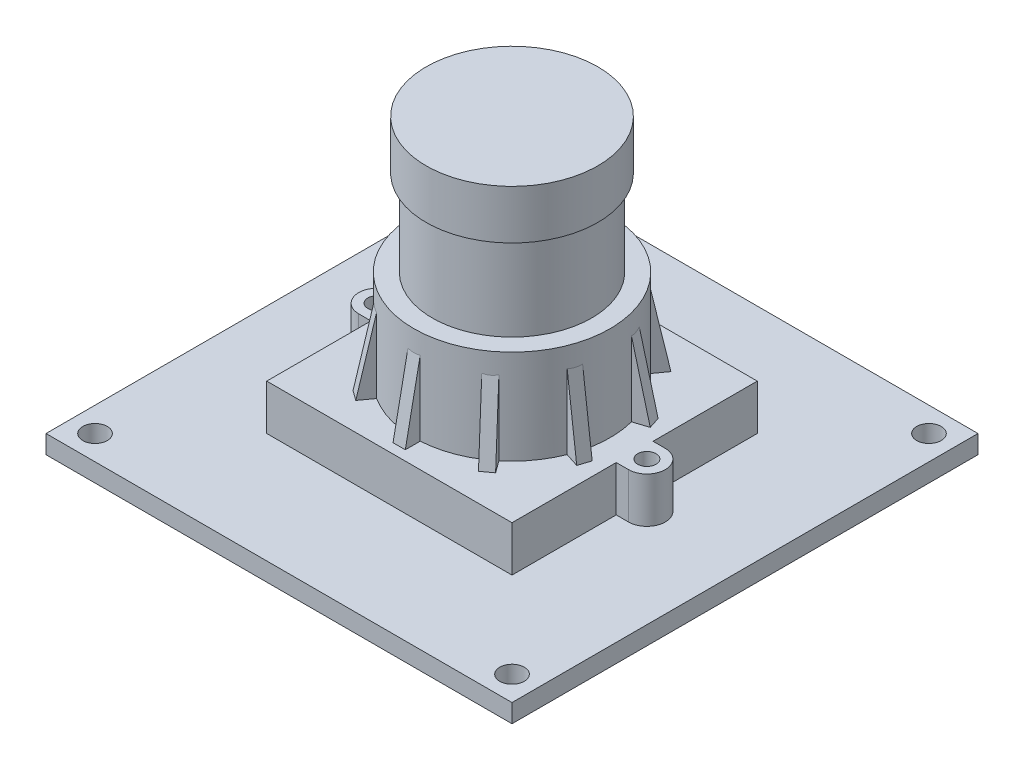
SolidWorks part; units mm, degrees
material "ABS"
ref_plane "前视基准面" through (0, 0, 0) normal (0, 0, 1) x (1, 0, 0)
ref_plane "上视基准面" through (0, 0, 0) normal (0, 1, 0) x (1, 0, 0)
ref_plane "右视基准面" through (0, 0, 0) normal (1, 0, 0) x (0, 0, -1)
sketch "草图1" plane through (0, 0, 0) normal (0, 1, 0) x (1, 0, 0)
  line L0 (0, 19) -> (0, -19) construction
  line L1 (-19, -19) -> (19, -19)
  line L2 (-19, -19) -> (-19, 19)
  line L3 (-19, 19) -> (19, 19)
  line L4 (19, -19) -> (19, 19)
  line L5 (-19, -19) -> (19, 19) construction
  line L6 (-19, 19) -> (19, -19) construction
  line L7 (-19, 0) -> (19, 0) construction
  circle A0 centre (-17, 17) radius 1
  circle A2 centre (17, 17) radius 1
  circle A3 centre (17, -17) radius 1
  circle A4 centre (-17, -17) radius 1
  point P0 (0, 0)
  dimension "D4" = 2
  dimension "D1" = 38
  dimension "D2" = 38
  dimension "D3" = 34
extrude "凸台-拉伸1" add sketch "草图1" along normal blind 1.5
sketch "草图2" plane through (0, 1.5, 0) normal (0, 1, 0) x (1, 0, 0)
  line L0 (0, 10) -> (0, -10) construction
  line L1 (-10, -10) -> (10, -10)
  line L2 (-10, -10) -> (-10, -1.5)
  line L3 (-10, 10) -> (10, 10)
  line L4 (10, -10) -> (10, 10) construction
  line L5 (-10, -10) -> (10, 10) construction
  line L6 (-10, 10) -> (10, -10) construction
  line L7 (-10, 0) -> (10, 0) construction
  line L8 (10, 1.5) -> (11, 1.5)
  line L9 (10, -1.5) -> (11, -1.5)
  line L10 (-10, -1.5) -> (-11, -1.5)
  line L11 (-10, 1.5) -> (-11, 1.5)
  line L12 (-10, 1.5) -> (-10, 10)
  line L13 (10, 1.5) -> (10, 10)
  line L14 (10, -1.5) -> (10, -10)
  arc A0 (11, -1.5) -> (11, 1.5) centre (11, 0) ccw
  circle A1 centre (11, 0) radius 0.75
  circle A2 centre (-11, 0) radius 0.75
  arc A3 (-11, -1.5) -> (-11, 1.5) centre (-11, 0) cw
  point P0 (0, 0)
  dimension "D4" = 1.5
  dimension "D5" = 1.5
  dimension "D1" = 20
  dimension "D2" = 20
  dimension "D3" = 11
extrude "凸台-拉伸2" add sketch "草图2" along normal blind 3.7
sketch "Sketch1" plane through (0, 5.2, 0) normal (0, 1, 0) x (1, 0, 0)
  circle A0 centre (0, 0) radius 8
  dimension "D1" = 16
extrude "Boss-Extrude1" add sketch "Sketch1" along normal blind 7.7
sketch "Sketch4" plane through (0, 0, 0) normal (1, 0, 0) x (0, 0, -1)
  line L0 (8, 11.2) -> (9.2, 5.2)
  line L1 (8, 5.2) -> (8, 12.9) construction
  line L2 (1.5, 5.2) -> (10, 5.2) construction
  dimension "D1" = 6
  dimension "D2" = 1.2
rib "Rib1" sketch "Sketch4" sketch "Sketch4" thickness 1 extrusion direction parallel to sketch draft on no parameters "D1"=1
pattern_circular "CirPattern1" count 10 every 36 about axis through (0, 0, 0) along (0, 1, 0) of "Rib1"
sketch "Sketch5" plane through (0, 0, 0) normal (1, 0, 0) x (0, 0, -1)
  line L0 (0, 12.9) -> (0, 27.614) construction
  line L1 (8, 12.9) -> (-8, 12.9) construction
  line L2 (0, 23.9) -> (7, 23.9)
  line L3 (7, 23.9) -> (7, 19.9)
  line L4 (7, 19.9) -> (6.5, 19.9)
  line L5 (6.5, 19.9) -> (6.5, 12.9)
  line L6 (6.5, 12.9) -> (0, 12.9)
  line L7 (0, 12.9) -> (0, 23.9)
  dimension "D1" = 7
  dimension "D2" = 11
  dimension "D3" = 4
  dimension "D4" = 6.5
revolve "Revolve1" add sketch "Sketch5" angle 360 about L0
